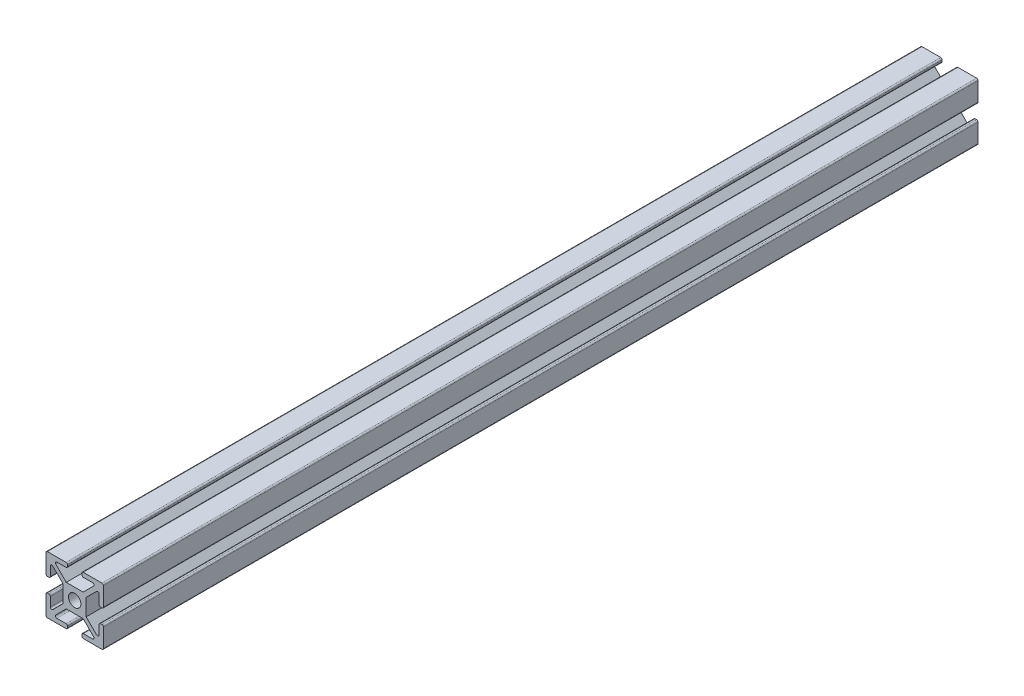
SolidWorks part; units mm, degrees
material "6061 Alloy"
ref_plane "Front Plane" through (0, 0, 0) normal (0, 0, 1) x (1, 0, 0)
ref_plane "Top Plane" through (0, 0, 0) normal (0, 1, 0) x (1, 0, 0)
ref_plane "Right Plane" through (0, 0, 0) normal (1, 0, 0) x (0, 0, -1)
sketch "Sketch1" plane through (0, 0, 0) normal (0, 0, 1) x (1, 0, 0)
  line L0 (-10, 2.5) -> (-8.5, 2.5)
  line L1 (-2.9393, 4) -> (0, 4)
  line L2 (-2.5, 10) -> (-10, 10)
  line L3 (-7.4393, 8.5) -> (-2.9393, 4)
  line L4 (-2.5, 8.5) -> (-7.4393, 8.5)
  line L5 (-8.5, 2.5) -> (-8.5, 7.4393)
  line L6 (-8.5, 7.4393) -> (-4, 2.9393)
  line L7 (-4, 2.9393) -> (-4, 0)
  line L8 (-4, 0) -> (-10, 0) construction
  line L9 (0, 10) -> (0, -10) construction
  line L10 (-10, 10) -> (0, 0) construction
  line L11 (-10, 2.5) -> (-10, 10)
  line L12 (-2.5, 10) -> (-2.5, 8.5)
  line L13 (-2.5, 10) -> (0, 10) construction
  line L14 (-10, 2.5) -> (-10, 0) construction
  line L15 (2.9393, 4) -> (0, 4)
  line L16 (4, 2.9393) -> (4, 0)
  line L17 (8.5, 7.4393) -> (4, 2.9393)
  line L18 (8.5, 2.5) -> (8.5, 7.4393)
  line L19 (10, 2.5) -> (8.5, 2.5)
  line L20 (10, 2.5) -> (10, 10)
  line L21 (2.5, 10) -> (10, 10)
  line L22 (2.5, 10) -> (2.5, 8.5)
  line L23 (2.5, 8.5) -> (7.4393, 8.5)
  line L24 (7.4393, 8.5) -> (2.9393, 4)
  line L25 (4, -2.9393) -> (4, 0)
  line L26 (2.9393, -4) -> (0, -4)
  line L27 (7.4393, -8.5) -> (2.9393, -4)
  line L28 (2.5, -8.5) -> (7.4393, -8.5)
  line L29 (2.5, -10) -> (2.5, -8.5)
  line L30 (2.5, -10) -> (10, -10)
  line L31 (10, -2.5) -> (10, -10)
  line L32 (10, -2.5) -> (8.5, -2.5)
  line L33 (8.5, -2.5) -> (8.5, -7.4393)
  line L34 (8.5, -7.4393) -> (4, -2.9393)
  line L35 (-2.9393, -4) -> (0, -4)
  line L36 (-4, -2.9393) -> (-4, 0)
  line L37 (-8.5, -7.4393) -> (-4, -2.9393)
  line L38 (-8.5, -2.5) -> (-8.5, -7.4393)
  line L39 (-10, -2.5) -> (-8.5, -2.5)
  line L40 (-10, -2.5) -> (-10, -10)
  line L41 (-2.5, -10) -> (-10, -10)
  line L42 (-2.5, -10) -> (-2.5, -8.5)
  line L43 (-2.5, -8.5) -> (-7.4393, -8.5)
  line L44 (-7.4393, -8.5) -> (-2.9393, -4)
  circle A0 centre (0, 0) radius 2.15
  point P53 (0, 0)
  dimension "D2" = 4.3
  dimension "D1" = 10
  dimension "D3" = 2.5
  dimension "D4" = 1.5
  dimension "D5" = 1.5
  dimension "D6" = 4
  dimension "D7" = 4
extrude "Boss-Extrude1" add sketch "Sketch1" along normal blind 304.8
fillet "Fillet1" radius 0.5 28 edges at (8.5, 2.5, 152.4) (2.5, 8.5, 152.4) (2.5, 10, 152.4) (2.5, -10, 152.4) (-10, 2.5, 152.4) (-8.5, -7.4393, 152.4) (-10, -10, 152.4) (-8.5, 7.4393, 152.4) (-7.4393, 8.5, 152.4) (7.4393, 8.5, 152.4) (8.5, -7.4393, 152.4) (7.4393, -8.5, 152.4) (-7.4393, -8.5, 152.4) (2.5, -8.5, 152.4) (-2.5, -10, 152.4) (-2.5, -8.5, 152.4) (10, -10, 152.4) (8.5, -2.5, 152.4) (10, -2.5, 152.4) (10, 2.5, 152.4) (-10, -2.5, 152.4) (-8.5, -2.5, 152.4) (-8.5, 2.5, 152.4) (-2.5, 8.5, 152.4) (-2.5, 10, 152.4) (-10, 10, 152.4) (10, 10, 152.4) (8.5, 7.4393, 152.4)
equation "\"12n\"=18"
